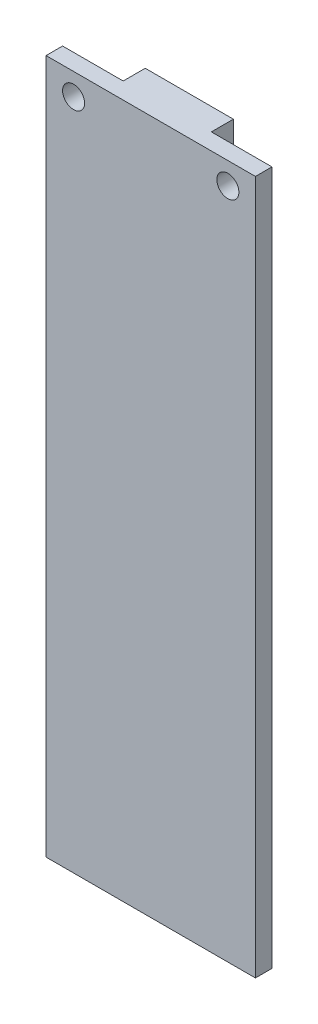
SolidWorks part; units mm, degrees
ref_plane "Plan de face" through (0, 0, 0) normal (0, 0, 1) x (1, 0, 0)
ref_plane "Plan de dessus" through (0, 0, 0) normal (0, 1, 0) x (1, 0, 0)
ref_plane "Plan de droite" through (0, 0, 0) normal (1, 0, 0) x (0, 0, -1)
sketch "Esquisse1" plane through (0, 0, 0) normal (0, 0, 1) x (1, 0, 0)
  line L0 (0, 31.5) -> (0, -31.5) construction
  line L1 (-9.5, -31.5) -> (9.5, -31.5)
  line L2 (-9.5, -31.5) -> (-9.5, 31.5)
  line L3 (-9.5, 31.5) -> (9.5, 31.5)
  line L4 (9.5, -31.5) -> (9.5, 31.5)
  line L5 (-9.5, -31.5) -> (9.5, 31.5) construction
  line L6 (-9.5, 31.5) -> (9.5, -31.5) construction
  circle A0 centre (-7, 29.5) radius 1
  circle A1 centre (7, 29.5) radius 1
  point P0 (0, 0)
  point P12 (0, 0)
  dimension "D3" = 2
  dimension "D1" = 63
  dimension "D2" = 19
  dimension "D4" = 14
  dimension "D5" = 2
extrude "Boss.-Extru.1" add sketch "Esquisse1" along normal blind 1.5
sketch "Esquisse2" plane through (0, 0, 0) normal (0, 0, -1) x (-1, 0, 0)
  line L0 (-4, 31.5) -> (-4, 27.5)
  line L1 (-9.5, 31.5) -> (9.5, 31.5) construction
  line L2 (-3, 26.5) -> (3, 26.5)
  line L3 (4, 27.5) -> (4, 31.5)
  line L4 (4, 31.5) -> (-4, 31.5)
  arc A0 (3, 26.5) -> (4, 27.5) centre (3, 27.5) ccw
  arc A1 (-4, 27.5) -> (-3, 26.5) centre (-3, 27.5) ccw
  point P5 (0, 31.5)
  point P9 (4, 26.5)
  point P12 (-4, 26.5)
  dimension "D3" = 1
  dimension "D1" = 8
  dimension "D2" = 5
extrude "Boss.-Extru.2" add sketch "Esquisse2" along normal blind 2
